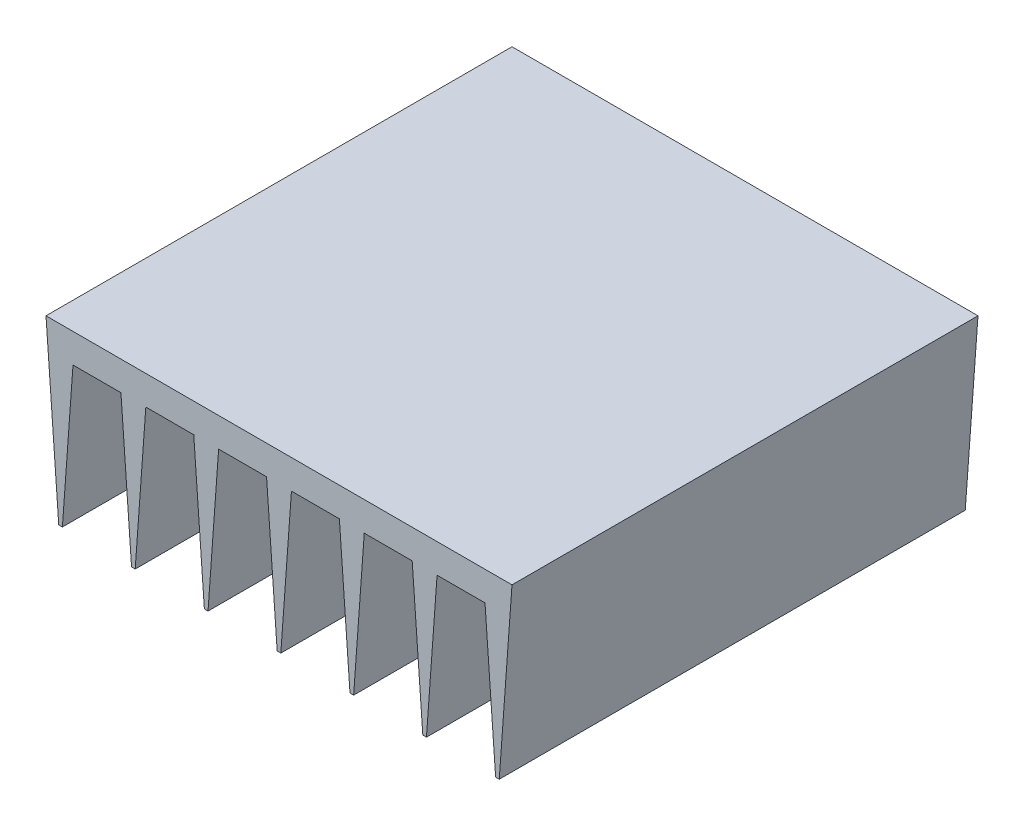
SolidWorks part; units mm, degrees
material "1060 Alloy"
ref_plane "Front Plane" through (0, 0, 0) normal (0, 0, 1) x (1, 0, 0)
ref_plane "Top Plane" through (0, 0, 0) normal (0, 1, 0) x (1, 0, 0)
ref_plane "Right Plane" through (0, 0, 0) normal (1, 0, 0) x (0, 0, -1)
sketch "Sketch1" plane through (0, 0, 0) normal (0, 0, 1) x (1, 0, 0)
  line L0 (-23.8125, 38.8339) -> (-23.8125, -41.3095) construction
  line L1 (-25.4, 0) -> (-24.0109, -19.05)
  line L2 (-22.4565, -3.175) -> (-23.6141, -19.05)
  line L3 (-24.0109, -19.05) -> (-23.6141, -19.05)
  line L4 (-17.231, -3.175) -> (-16.0734, -19.05)
  line L5 (-14.519, -3.175) -> (-15.6766, -19.05)
  line L6 (-16.0734, -19.05) -> (-15.6766, -19.05)
  line L7 (-9.2935, -3.175) -> (-8.1359, -19.05)
  line L8 (-6.5815, -3.175) -> (-7.7391, -19.05)
  line L9 (-8.1359, -19.05) -> (-7.7391, -19.05)
  line L10 (-1.356, -3.175) -> (-0.1984, -19.05)
  line L11 (1.356, -3.175) -> (0.1984, -19.05)
  line L12 (-0.1984, -19.05) -> (0.1984, -19.05)
  line L13 (6.5815, -3.175) -> (7.7391, -19.05)
  line L14 (9.2935, -3.175) -> (8.1359, -19.05)
  line L15 (7.7391, -19.05) -> (8.1359, -19.05)
  line L16 (14.519, -3.175) -> (15.6766, -19.05)
  line L17 (17.231, -3.175) -> (16.0734, -19.05)
  line L18 (15.6766, -19.05) -> (16.0734, -19.05)
  line L19 (22.4565, -3.175) -> (23.6141, -19.05)
  line L20 (25.4, 0) -> (24.0109, -19.05)
  line L21 (23.6141, -19.05) -> (24.0109, -19.05)
  line L22 (-25.4, 0) -> (25.4, 0)
  line L24 (-22.4565, -3.175) -> (-17.231, -3.175)
  line L26 (-14.519, -3.175) -> (-9.2935, -3.175)
  line L27 (-6.5815, -3.175) -> (-1.356, -3.175)
  line L28 (1.356, -3.175) -> (6.5815, -3.175)
  line L29 (9.2935, -3.175) -> (14.519, -3.175)
  line L30 (17.231, -3.175) -> (22.4565, -3.175)
  dimension "D2" = 0.3969
  dimension "D6" = 7
extrude "Boss-Extrude1" add sketch "Sketch1" along normal mid plane 50.8
